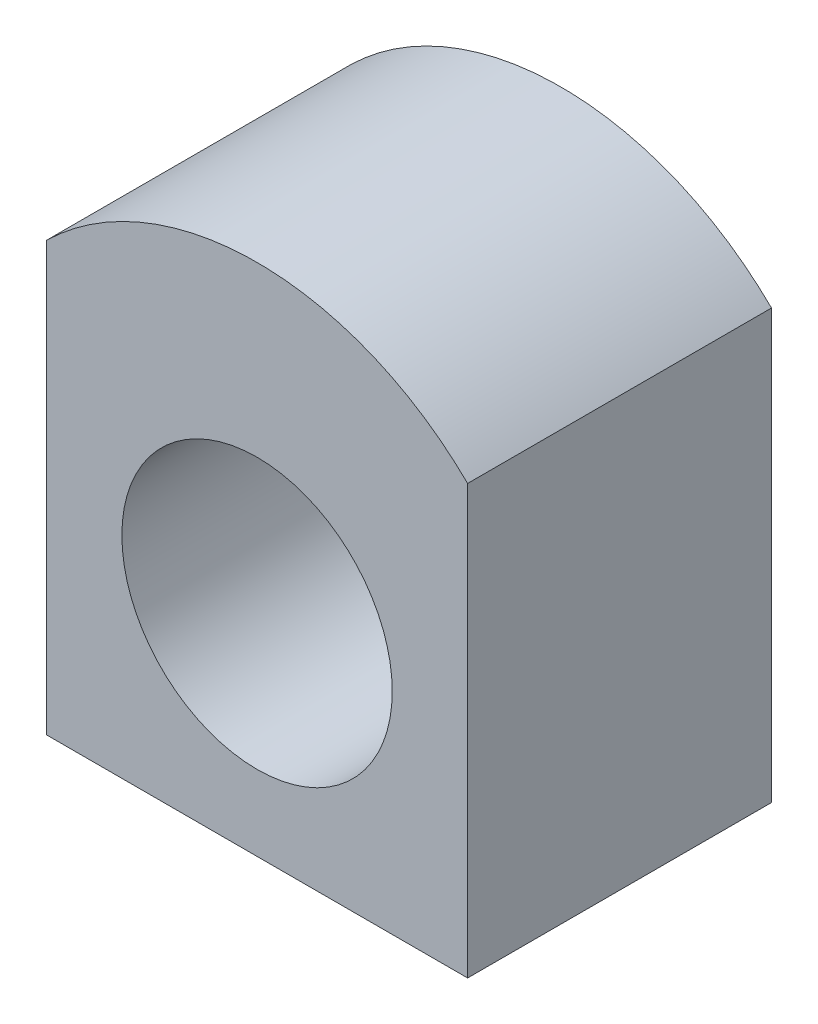
SolidWorks part; units mm, degrees
ref_plane "Спереди" through (0, 0, 0) normal (0, 0, 1) x (1, 0, 0)
ref_plane "Сверху" through (0, 0, 0) normal (0, 1, 0) x (1, 0, 0)
ref_plane "Справа" through (0, 0, 0) normal (1, 0, 0) x (0, 0, -1)
sketch "Эскиз1" plane through (0, 0, 0) normal (0, 0, 1) x (1, 0, 0)
  line L0 (-8.8, 0) -> (8.8, 0)
  line L1 (8.8, 0) -> (8.8, 17.9)
  line L2 (-8.8, 0) -> (-8.8, 17.9)
  arc A0 (-8.8, 17.9) -> (8.8, 17.9) centre (0, 8.9444) cw
  point P3 (0, 21.5)
  point P8 (0, 21.5)
  dimension "D1" = 17.6
  dimension "D2" = 8.8
  dimension "D3" = 21.5
  dimension "D4" = 17.9
extrude "Бобышка-Вытянуть1" add sketch "Эскиз1" along normal blind 12.7
sketch "Эскиз2" plane through (0, 0, 12.7) normal (0, 0, 1) x (1, 0, 0)
  circle A0 centre (0, 8.8) radius 5.65
  dimension "D1" = 11.3
  dimension "D2" = 8.8
extrude "Вырез-Вытянуть1" cut sketch "Эскиз2" against normal through all
